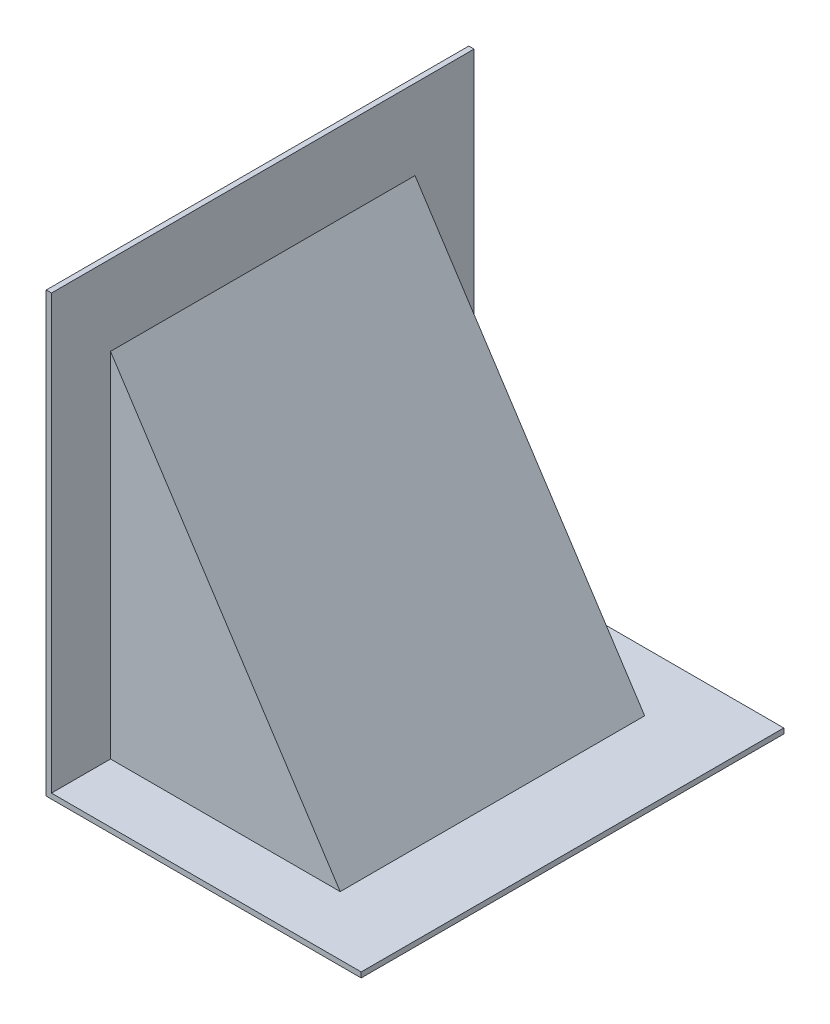
SolidWorks part; units mm, degrees
ref_plane "Front Plane" through (0, 0, 0) normal (0, 0, 1) x (1, 0, 0)
ref_plane "Top Plane" through (0, 0, 0) normal (0, 1, 0) x (1, 0, 0)
ref_plane "Right Plane" through (0, 0, 0) normal (1, 0, 0) x (0, 0, -1)
sketch "Sketch1" plane through (0, 0, 0) normal (0, 0, 1) x (1, 0, 0)
  line L0 (0, 0) -> (87.5, 0)
  line L1 (87.5, 0) -> (0, 134.5)
  line L2 (0, 134.5) -> (0, 0)
  dimension "D1" = 87.5
  dimension "D2" = 134.5
extrude "Boss-Extrude1" add sketch "Sketch1" along normal blind 116
sketch "Sketch2" plane through (0, 0, 0) normal (0, -1, 0) x (-1, 0, 0)
  line L0 (0, -58) -> (-87.5, -58) construction
  line L1 (0, -116) -> (0, 0) construction
  line L2 (-87.5, -116) -> (-87.5, 0) construction
  line L4 (-118, 22.5) -> (0, 22.5)
  line L5 (-118, 22.5) -> (-118, -138.5)
  line L6 (-118, -138.5) -> (0, -138.5)
  line L7 (0, 22.5) -> (0, -138.5)
  line L8 (-118, 22.5) -> (0, -138.5) construction
  line L9 (-118, -138.5) -> (0, 22.5) construction
  point P6 (-59, -58)
  dimension "D1" = 118
  dimension "D2" = 161
extrude "Boss-Extrude2" add sketch "Sketch2" along normal blind 2
sketch "Sketch3" plane through (0, 0, 0) normal (-1, 0, 0) x (0, 0, 1)
  line L0 (58, 134.5) -> (58, -2) construction
  line L1 (116, 134.5) -> (0, 134.5) construction
  line L2 (138.5, -2) -> (-22.5, -2) construction
  line L4 (-22.5, 165) -> (138.5, 165)
  line L5 (-22.5, 165) -> (-22.5, -2)
  line L6 (-22.5, -2) -> (138.5, -2)
  line L7 (138.5, 165) -> (138.5, -2)
  line L8 (-22.5, 165) -> (138.5, -2) construction
  line L9 (-22.5, -2) -> (138.5, 165) construction
  point P6 (58, 81.5)
  point P12 (138.5, -2)
  dimension "D1" = 167
extrude "Boss-Extrude4" add sketch "Sketch3" along normal blind 2
